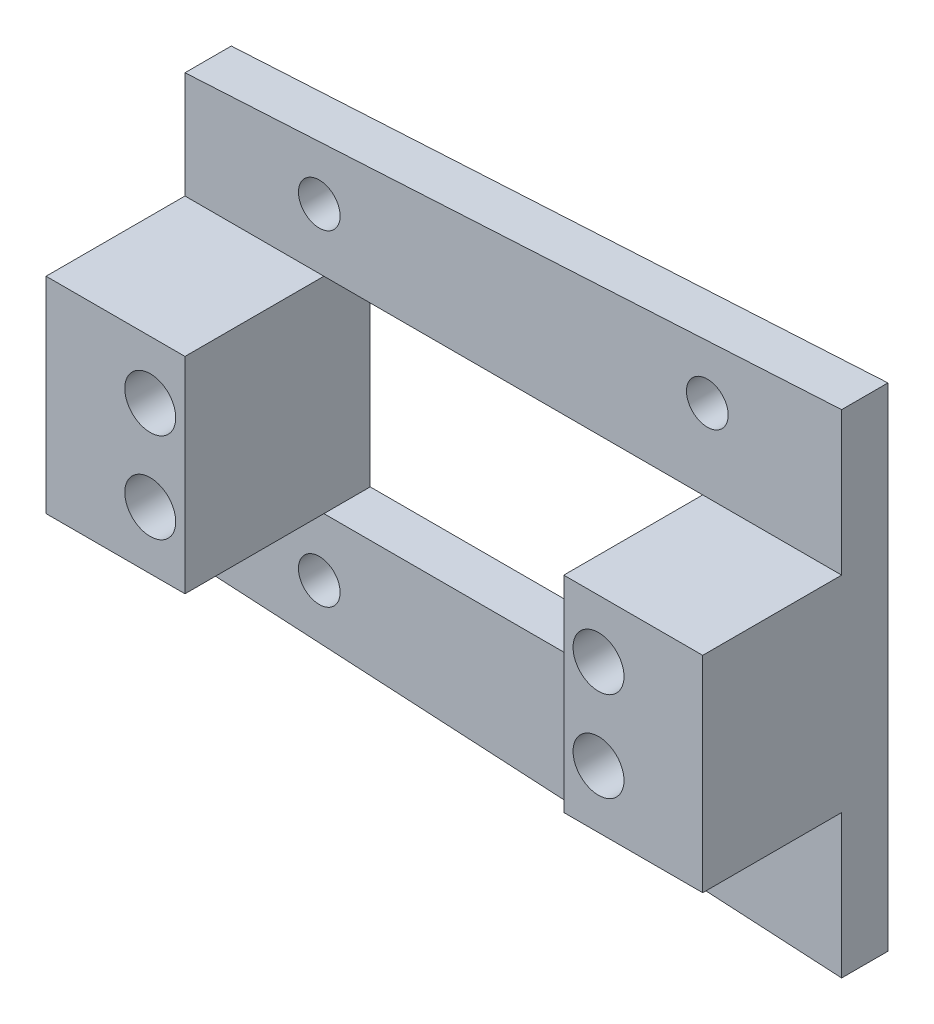
SolidWorks part; units mm, degrees
ref_plane "Front Plane" through (0, 0, 0) normal (0, 0, 1) x (1, 0, 0)
ref_plane "Top Plane" through (0, 0, 0) normal (0, 1, 0) x (1, 0, 0)
ref_plane "Right Plane" through (0, 0, 0) normal (1, 0, 0) x (0, 0, -1)
sketch "Sketch1" plane through (0, 0, 0) normal (0, 0, 1) x (1, 0, 0)
  line L0 (-26.95, 23.1) -> (26.95, 26.1)
  line L1 (26.95, 10.1) -> (20.45, 10.1)
  line L2 (26.95, 10.1) -> (26.95, -10.1)
  line L3 (26.95, -10.1) -> (-26.95, -10.1)
  line L4 (-26.95, 10.1) -> (-26.95, -10.1)
  line L5 (26.95, 10.1) -> (-26.95, -10.1) construction
  line L6 (26.95, -10.1) -> (-26.95, 10.1) construction
  line L7 (-26.95, 10.1) -> (-28.4904, 10.1)
  line L8 (0, 27.4314) -> (0, -28.5155) construction
  line L9 (0, 0) -> (66.5046, 0) construction
  line L10 (26.95, -10.1) -> (-26.95, -10.1)
  line L11 (-26.95, 23.1) -> (-26.95, 12.1)
  line L12 (-26.95, 12.1) -> (26.95, 12.1)
  line L13 (26.95, 12.1) -> (26.95, 26.1)
  line L14 (-20.95, -17.6) -> (21.9399, -19.9872) construction
  line L15 (26.95, -12.1) -> (26.95, -26.1)
  line L16 (-26.95, -12.1) -> (26.95, -12.1)
  line L17 (-26.95, -23.1) -> (-26.95, -12.1)
  line L18 (26.95, -10.1) -> (-26.95, -10.1)
  line L19 (-20.95, 17.6) -> (21.9399, 19.9872) construction
  line L20 (-26.95, -23.1) -> (26.95, -26.1)
  line L21 (-20.45, -34.5128) -> (-20.45, 33.8284) construction
  line L22 (-20.45, -10.1) -> (-20.45, 10.1)
  line L23 (35.45, -10.1) -> (35.45, 10.1)
  line L24 (-20.45, -10.1) -> (-35.45, -10.1)
  line L25 (-20.45, -10.1) -> (-20.45, 10.1)
  line L26 (-20.45, 10.1) -> (-35.45, 10.1)
  line L27 (-35.45, -10.1) -> (-35.45, 10.1)
  line L28 (20.45, 10.1) -> (35.45, 10.1)
  line L29 (20.45, -10.1) -> (20.45, 10.1)
  line L30 (20.45, -10.1) -> (35.45, -10.1)
  line L31 (20.45, -10.1) -> (20.45, 10.1)
  line L32 (26.95, 10.1) -> (28.4904, 10.1)
  line L33 (26.95, 10.1) -> (26.95, -10.1)
  line L34 (-20.45, 11.1) -> (20.45, 11.1)
  line L35 (20.45, 11.1) -> (20.45, 10.1)
  line L36 (-20.45, 11.1) -> (-20.45, 10.1)
  line L37 (-20.45, 10.1) -> (-26.95, 10.1)
  line L38 (20.45, -10.1) -> (20.45, -11.1)
  line L39 (20.45, -11.1) -> (-20.45, -11.1)
  line L40 (-20.45, -11.1) -> (-20.45, -10.1)
  line L41 (-26.95, 23.1) -> (-35.45, 22.6269)
  line L42 (-20.45, 11.1) -> (20.45, 11.1)
  line L43 (-20.45, 11.1) -> (-20.45, -11.1)
  line L44 (-20.45, -11.1) -> (20.45, -11.1)
  line L45 (20.45, 11.1) -> (20.45, -11.1)
  line L46 (-20.45, 11.1) -> (-35.45, 11.1)
  line L47 (-20.45, 11.1) -> (-20.45, -11.1)
  line L48 (-20.45, -11.1) -> (-35.45, -11.1)
  line L49 (-35.45, 11.1) -> (-35.45, -11.1)
  line L50 (20.45, 11.1) -> (35.45, 11.1)
  line L51 (20.45, 11.1) -> (20.45, -11.1)
  line L52 (20.45, -11.1) -> (35.45, -11.1)
  line L53 (35.45, 11.1) -> (35.45, -11.1)
  line L54 (-35.45, 22.6269) -> (-35.45, 11.1)
  line L55 (26.95, 26.1) -> (35.45, 26.5731)
  line L56 (35.45, 26.5731) -> (35.45, 11.1)
  line L57 (-35.45, -11.1) -> (-35.45, -22.6269)
  line L58 (-35.45, -22.6269) -> (35.45, -26.5731)
  line L59 (35.45, -26.5731) -> (35.45, -11.1)
  circle A0 centre (-20.95, 17.6) radius 2.25
  circle A1 centre (20.95, 19.9321) radius 2.25
  circle A2 centre (20.95, -19.9321) radius 2.25
  circle A3 centre (-20.95, -17.6) radius 2.25
  circle A4 centre (-24.2, 4.86) radius 2.75
  circle A5 centre (-24.2, -4.86) radius 2.75
  circle A6 centre (24.2, -4.86) radius 2.75
  circle A7 centre (24.2, 4.86) radius 2.75
  point P0 (0, 0)
  point P5 (-26.95, 12.1)
  point P6 (-26.95, 23.1)
  point P29 (26.95, -26.1)
  point P30 (-26.95, -23.1)
  point P31 (26.95, 26.1)
  point P32 (10.55, 0)
  point P34 (-26.95, -12.1)
  point P36 (-24.2, -4.86)
  point P44 (-24.2, 4.86)
  point P60 (24.2, 4.86)
  point P61 (24.2, -4.86)
  dimension "D3" = 4.5
  dimension "D15" = 5.5
  dimension "D16" = 5.5
  dimension "D1" = 20.2
  dimension "D2" = 16.4
  dimension "D4" = 53.9
  dimension "D5" = 2
  dimension "D6" = 11
  dimension "D7" = 14
  dimension "D8" = 6
  dimension "D9" = 5.5
  dimension "D10" = 6
  dimension "D11" = 5.24
  dimension "D12" = 5.24
  dimension "D13" = 2.75
  dimension "D14" = 2.75
  dimension "D17" = 6.5
  dimension "D18" = 15
  dimension "D19" = 1
  dimension "D20" = 1
extrude "Boss-Extrude4" add sketch "Sketch1" along normal blind 20 contours L56 L55 L13 L12 L11 L41 L54 L46 L34 L50 | L12 L13 L0 L11 A1 A0 | L53 L50 L35 L1 L28 | L46 L49 L26 L7 L36 | L27 L24 L4 L7 L26 | L4 A5 L18 L22 L26 A4 | L24 L49 L48 L40 L18 | L58 L59 L52 L39 L48 L57 L17 L16 L15 | L17 L20 L15 L16 A2 A3 | L2 L33 L30 L23 L28 | L33 A7 L2 L1 L29 L3 A6 | L53 L30 L3 L38 L52
sketch "Sketch4" plane through (0, 0, 20) normal (0, 0, 1) x (1, 0, 0)
  line L0 (-35.45, 22.6269) -> (-35.45, -22.6269) construction
  line L1 (-35.45, 11.1) -> (35.45, 11.1)
  line L2 (-35.45, 11.1) -> (-35.45, 26.5731)
  line L3 (-35.45, 26.5731) -> (35.45, 26.5731)
  line L4 (35.45, 11.1) -> (35.45, 26.5731)
  line L5 (20.45, 11.1) -> (-20.45, 11.1) construction
  line L6 (-20.45, -11.1) -> (20.45, -11.1) construction
  line L7 (-35.45, -11.1) -> (35.45, -11.1)
  line L8 (-35.45, -11.1) -> (-35.45, -26.5731)
  line L9 (-35.45, -26.5731) -> (35.45, -26.5731)
  line L10 (35.45, -11.1) -> (35.45, -26.5731)
extrude "Cut-Extrude1" cut sketch "Sketch4" against normal blind 15
